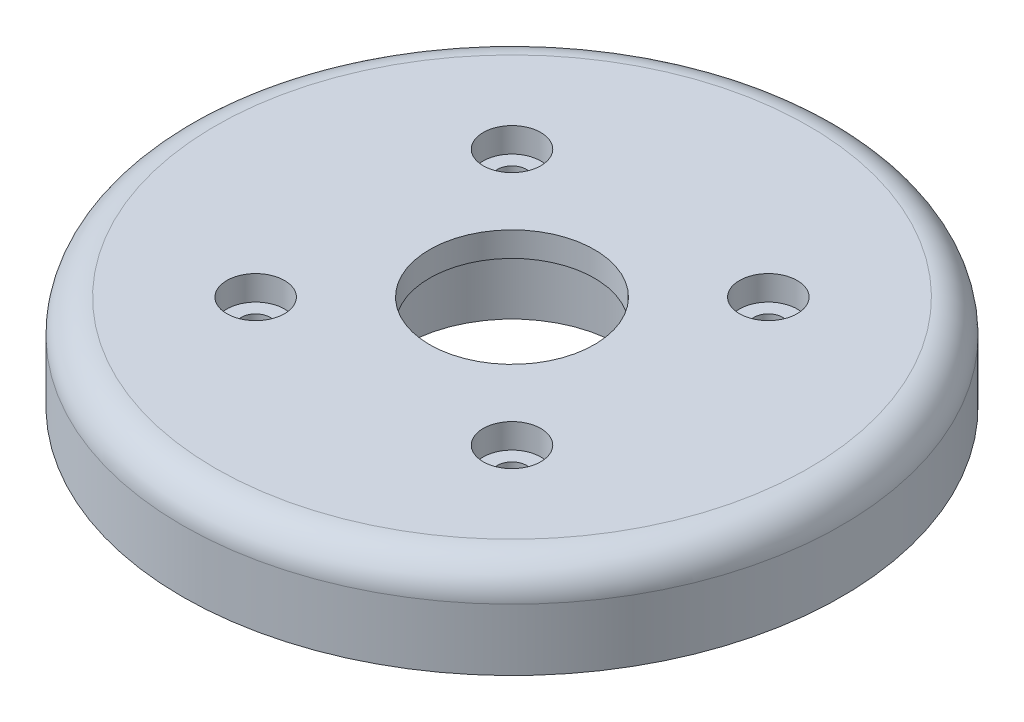
SolidWorks part; units mm, degrees
material "ABS"
ref_plane "Front Plane" through (0, 0, 0) normal (0, 0, 1) x (1, 0, 0)
ref_plane "Top Plane" through (0, 0, 0) normal (0, 1, 0) x (1, 0, 0)
ref_plane "Right Plane" through (0, 0, 0) normal (1, 0, 0) x (0, 0, -1)
sketch "Sketch1" plane through (0, 0, 0) normal (0, 1, 0) x (1, 0, 0)
  circle A0 centre (0, 0) radius 13
  circle A1 centre (0, 0) radius 40
  dimension "D5" = 26
  dimension "D1" = 80
extrude "Boss-Extrude1" add sketch "Sketch1" along normal blind 8.5
sketch "Sketch3" plane through (0, 8.5, 0) normal (0, 1, 0) x (1, 0, 0)
  line L0 (-1000, 0) -> (49000, 0) construction
  line L1 (-22.5194, 22.5194) -> (35332.4143, -35332.4143) construction
  circle A0 centre (-15.5563, 15.5563) radius 1.75
  circle A1 centre (15.5563, 15.5563) radius 1.75
  circle A2 centre (15.5563, -15.5563) radius 1.75
  circle A3 centre (-15.5563, -15.5563) radius 1.75
  point P16 (0, 0)
  dimension "D3" = 3.5
  dimension "D5" = 22
  dimension "D1" = 22
  dimension "D2" = 45
  dimension "D4" = 4
extrude "Cut-Extrude1" cut sketch "Sketch3" against normal through all
sketch "Sketch2" plane through (0, 8.5, 0) normal (0, 1, 0) x (1, 0, 0)
  circle A0 centre (0, 0) radius 10
  circle A1 centre (0, 0) radius 40
  circle A2 centre (0, 0) radius 40 construction
  circle A3 centre (-15.5563, 15.5563) radius 3.5
  circle A4 centre (15.5563, 15.5563) radius 3.5
  circle A5 centre (15.5563, -15.5563) radius 3.5
  circle A6 centre (-15.5563, -15.5563) radius 3.5
  dimension "D1" = 20
  dimension "D2" = 7
extrude "Boss-Extrude2" add sketch "Sketch2" along normal blind 3
fillet "Fillet1" radius 4 1 edges at (0, 11.5, 40)
